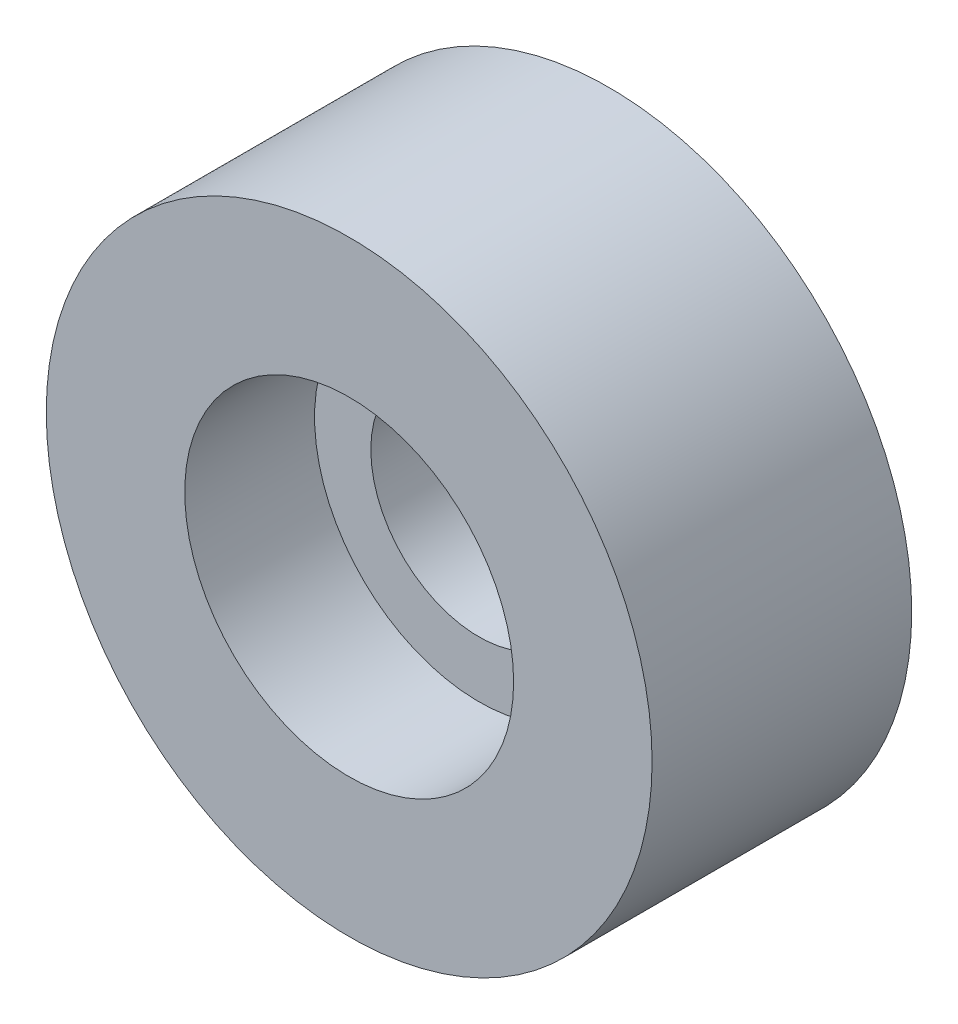
SolidWorks part; units mm, degrees
ref_plane "前视基准面" through (0, 0, 0) normal (0, 0, 1) x (1, 0, 0)
ref_plane "上视基准面" through (0, 0, 0) normal (0, 1, 0) x (1, 0, 0)
ref_plane "右视基准面" through (0, 0, 0) normal (1, 0, 0) x (0, 0, -1)
other "Configuration Table"
sketch "草图1" plane through (0, 0, 0) normal (0, 0, 1) x (1, 0, 0)
  circle A0 centre (0, 0) radius 3.5
  dimension "D1" = 7
extrude "凸台-拉伸1" add sketch "草图1" along normal blind 3
sketch "草图2" plane through (0, 0, 3) normal (0, 0, 1) x (1, 0, 0)
  circle A0 centre (0, 0) radius 1.9
  dimension "D1" = 3.8
extrude "切除-拉伸1" cut sketch "草图2" against normal blind 1.5
sketch "草图3" plane through (0, 0, 1.5) normal (0, 0, 1) x (1, 0, 0)
  circle A0 centre (0, 0) radius 1.25
extrude "切除-拉伸2" cut sketch "草图3" against normal through all
sketch "Sketch1" plane through (0, 0, 0) normal (0, 0, -1) x (-1, 0, 0)
  circle A0 centre (0, 0) radius 1.25
  circle A1 centre (0, 0) radius 1.05
  dimension "D1" = 2.5
  dimension "D2" = 2.1
extrude "Boss-Extrude1" add sketch "Sketch1" along normal blind 1 separate body
sketch "Sketch3" plane through (0, 0, 0) normal (0, 0, -1) x (-1, 0, 0)
  circle A0 centre (0, 0) radius 1.25
  circle A1 centre (0, 0) radius 2
  dimension "D1" = 4
extrude "Boss-Extrude2" add sketch "Sketch3" along normal blind 1
